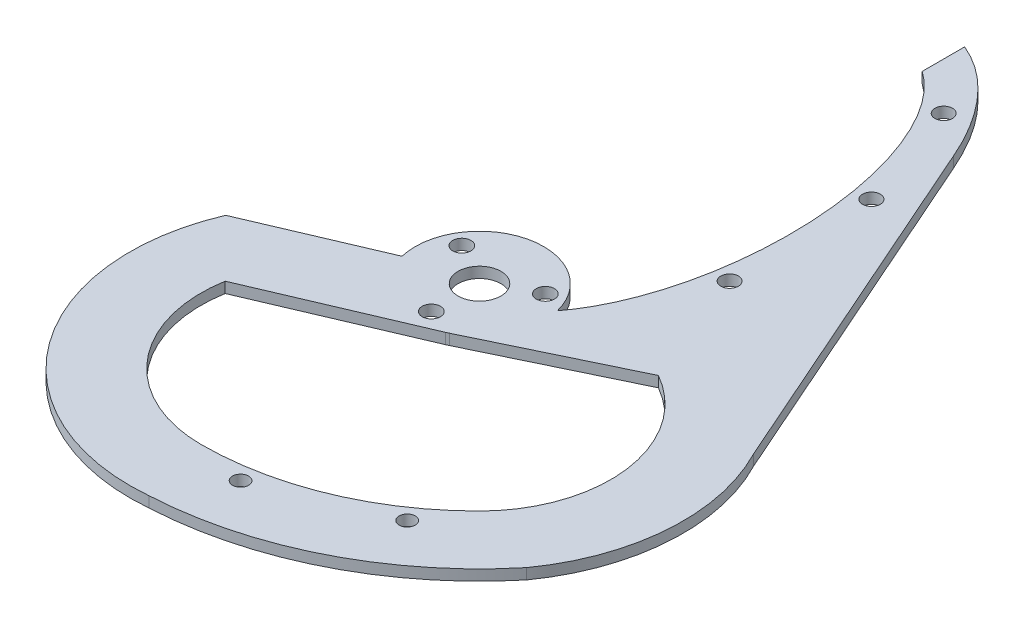
SolidWorks part; units mm, degrees
ref_plane "Спереди" through (0, 0, 0) normal (0, 0, 1) x (1, 0, 0)
ref_plane "Сверху" through (0, 0, 0) normal (0, 1, 0) x (1, 0, 0)
ref_plane "Справа" through (0, 0, 0) normal (1, 0, 0) x (0, 0, -1)
sketch "Эскиз1" plane through (0, 0, 0) normal (0, 1, 0) x (1, 0, 0)
  line L0 (0, 0) -> (0, -55) construction
  line L1 (9.5506, -54.1644) -> (0, 0) construction
  line L2 (0, 0) -> (35.7004, -86.1885) construction
  line L3 (53.1014, -1.9192) -> (23.6106, 64.8709)
  line L4 (0, 0) -> (0, 74) construction
  line L5 (0, 67) -> (0, 74) construction
  line L6 (-34.753, -12.6417) -> (-11.6687, -2.8004)
  line L7 (0, 0) -> (38.8909, -38.8909) construction
  line L8 (0, 0) -> (-20.1763, 11.6488) construction
  line L9 (0, 0) -> (0, -14.3061) construction
  line L10 (0, 0) -> (20.2825, 11.7101) construction
  line L11 (7, 83.5807) -> (7, 75.6552)
  line L12 (5.2014, -10.8141) -> (31.5467, 1.8574)
  line L13 (4.706, -11.0387) -> (-24.1439, -23.338)
  arc A0 (50.3205, -41.505) -> (3.4652, -65.1369) centre (0, 0) cw
  arc A1 (0, -52) -> (36.7696, -36.7696) centre (0, 0) ccw
  arc A2 (0, -55) -> (55, 0) centre (0, 0) ccw construction
  circle A3 centre (9.5506, -54.1644) radius 1.5
  circle A4 centre (31.5467, -45.0534) radius 1.5
  circle A5 centre (19.4454, -19.4454) radius 24.5 construction
  circle A6 centre (0, 0) radius 4
  arc A7 (4.706, -11.0387) -> (5.2014, -10.8141) centre (0, 0) ccw
  arc A8 (11.648, 2.8851) -> (-11.6687, -2.8004) centre (0, 0) ccw
  arc A9 (-3.7011, -11.415) -> (2.0838, -11.8177) centre (0, 0) ccw construction
  arc A10 (36.7696, -36.7696) -> (31.5467, 1.8574) centre (19.4454, -19.4454) ccw
  arc A11 (-34.753, -12.6417) -> (3.4652, -65.1369) centre (0, -27.5) ccw
  arc A12 (50.3205, -41.505) -> (53.1014, -1.9192) centre (19.4454, -19.4454) ccw
  circle A13 centre (0, 0) radius 9 construction
  circle A14 centre (0, -9) radius 1.7
  circle A15 centre (-7.7942, 4.5) radius 1.7
  circle A16 centre (0, -27.5) radius 24.5 construction
  circle A17 centre (0, 0) radius 10.7 construction
  arc A18 (0, -52) -> (-24.1439, -23.338) centre (0, -27.5) cw
  circle A19 centre (7.7942, 4.5) radius 1.7
  ellipse E1 centre (0, 37) end of major axis (0, 78) minor radius 21 (11.648, 2.8851) -> (7, 75.6552) ccw
  ellipse E2 centre (0, 37) end of major axis (0, -11) minor radius 29 (23.6106, 64.8709) -> (7, 83.5807) ccw
  point P25 (-0.6653, 12.4183)
  dimension "D2" = 55
  dimension "D3" = 52
  dimension "D4" = 3
  dimension "D7" = 37
  dimension "D8" = 12
  dimension "D9" = 8
  dimension "D10" = 41
  dimension "D11" = 18
  dimension "D12" = 48
  dimension "D13" = 21.4
  dimension "D14" = 120
  dimension "D5" = 10
  dimension "D6" = 22.5
  dimension "D15" = 120
  dimension "D16" = 7
  dimension "D17" = 21
  dimension "D18" = 29
  dimension "D19" = 14
extrude "Бобышка-Вытянуть1" add sketch "Эскиз1" along normal blind 2
sketch "Эскиз2" plane through (0, 0, 0) normal (0, -1, 0) x (1, 0, 0)
  line L0 (0, 0) -> (0, -74) construction
  line L1 (0, -37) -> (47.6456, -9.4918) construction
  line L2 (0, -37) -> (23.5063, -87.4093) construction
  line L3 (0, -37) -> (48.7895, -65.1686) construction
  circle A0 centre (22.9372, -23.7572) radius 1.65
  circle A1 centre (15.7972, -70.8772) radius 1.65
  circle A2 centre (22.9372, -50.2428) radius 1.65
  ellipse E1 centre (0, -37) end of major axis (0, 8) minor radius 24 construction
  dimension "D3" = 3.3
  dimension "D4" = 3.3
  dimension "D5" = 3.3
  dimension "D1" = 120
  dimension "D2" = 25
  dimension "D6" = 60
  dimension "D7" = 37
  dimension "D8" = 45
  dimension "D9" = 24
extrude "Вырез-Вытянуть1" cut sketch "Эскиз2" against normal through all
